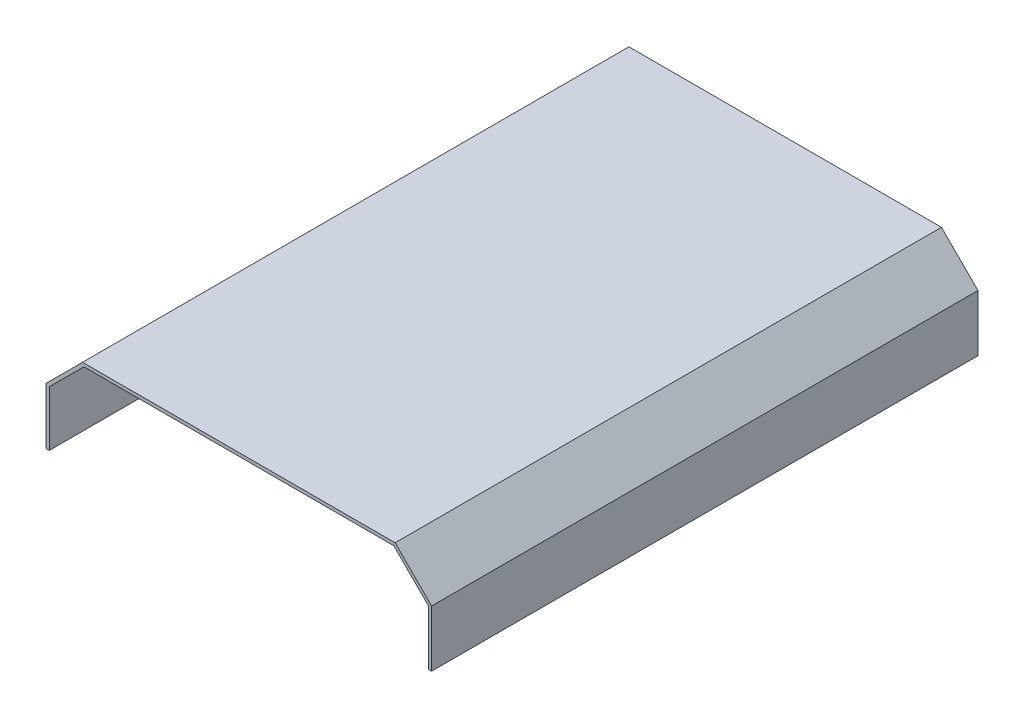
SolidWorks part; units mm, degrees
ref_plane "Plan de face" through (0, 0, 0) normal (0, 0, 1) x (1, 0, 0)
ref_plane "Plan de dessus" through (0, 0, 0) normal (0, 1, 0) x (1, 0, 0)
ref_plane "Plan de droite" through (0, 0, 0) normal (1, 0, 0) x (0, 0, -1)
sketch "Esquisse1" plane through (0, 0, 0) normal (0, 0, 1) x (1, 0, 0)
  line L0 (0, 0) -> (0, 33.79)
  line L1 (0, 33.79) -> (21.2132, 55.0032)
  line L2 (21.2132, 55.0032) -> (211.2132, 55.0032)
  line L3 (211.2132, 55.0032) -> (232.4264, 33.79)
  line L4 (232.4264, 33.79) -> (232.4264, 0)
  line L5 (-2, 0) -> (-2, 34.6184)
  line L6 (-2, 34.6184) -> (20.3848, 57.0032)
  line L7 (20.3848, 57.0032) -> (212.0416, 57.0032)
  line L8 (212.0416, 57.0032) -> (234.4264, 34.6184)
  line L9 (234.4264, 34.6184) -> (234.4264, 0)
  line L10 (-2, 0) -> (0, 0)
  line L11 (232.4264, 0) -> (234.4264, 0)
  dimension "D1" = 33.79
  dimension "D2" = 135
  dimension "D3" = 30
  dimension "D4" = 190
  dimension "D5" = 135
  dimension "D6" = 30
  dimension "D7" = 33.79
  dimension "D8" = 2
extrude "Boss.-Extru.2" add sketch "Esquisse1" along normal blind 335
